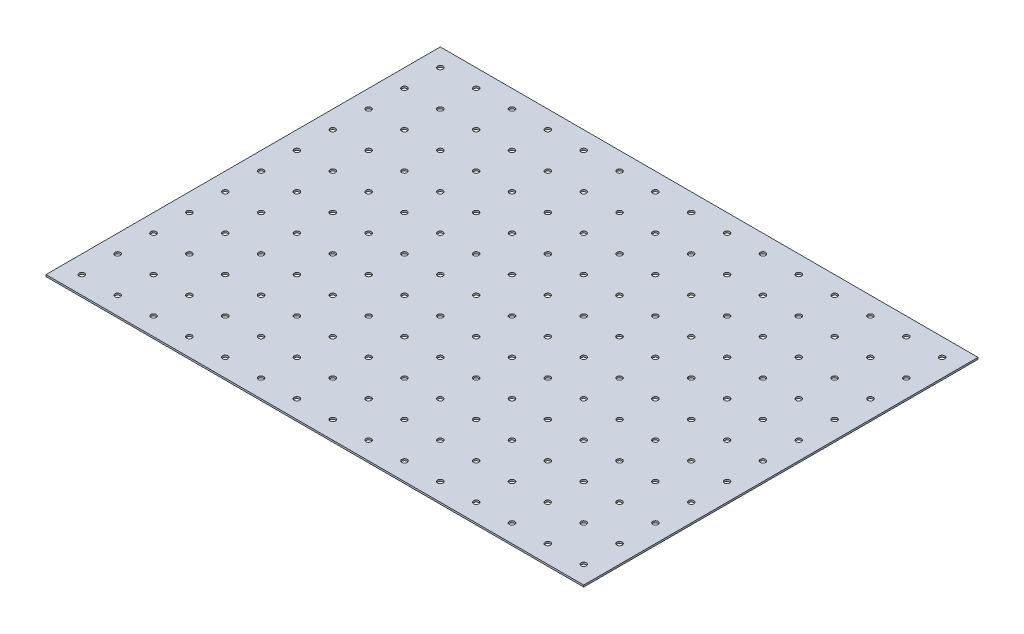
SolidWorks part; units mm, degrees
ref_plane "Front Plane" through (0, 0, 0) normal (0, 0, 1) x (1, 0, 0)
ref_plane "Top Plane" through (0, 0, 0) normal (0, 1, 0) x (1, 0, 0)
ref_plane "Right Plane" through (0, 0, 0) normal (1, 0, 0) x (0, 0, -1)
sketch "Sketch1" plane through (0, 0, 0) normal (0, 1, 0) x (1, 0, 0)
  line L1 (-92.944, 42.8224) -> (207.056, 42.8224)
  line L2 (-92.944, 42.8224) -> (-92.944, -177.1776)
  line L3 (-92.944, -177.1776) -> (207.056, -177.1776)
  line L4 (207.056, 42.8224) -> (207.056, -177.1776)
  dimension "D1" = 300
  dimension "D2" = 220
extrude "Boss-Extrude1" add sketch "Sketch1" along normal blind 1
sketch "Sketch2" plane through (0, 1, 0) normal (0, 1, 0) x (1, 0, 0)
  line L0 (207.056, 42.8224) -> (-92.944, 42.8224) construction
  line L1 (-92.944, 42.8224) -> (-92.944, -177.1776) construction
  circle A0 centre (-82.944, 32.8224) radius 1.5
  dimension "D1" = 3
  dimension "D2" = 10
  dimension "D3" = 10
extrude "Cut-Extrude1" cut sketch "Sketch2" against normal blind 1
pattern_linear "LPattern1" count 15 spacing 20 along (1, 0, 0) count 11 spacing 20 along (0, 0, 1) of "Cut-Extrude1"
